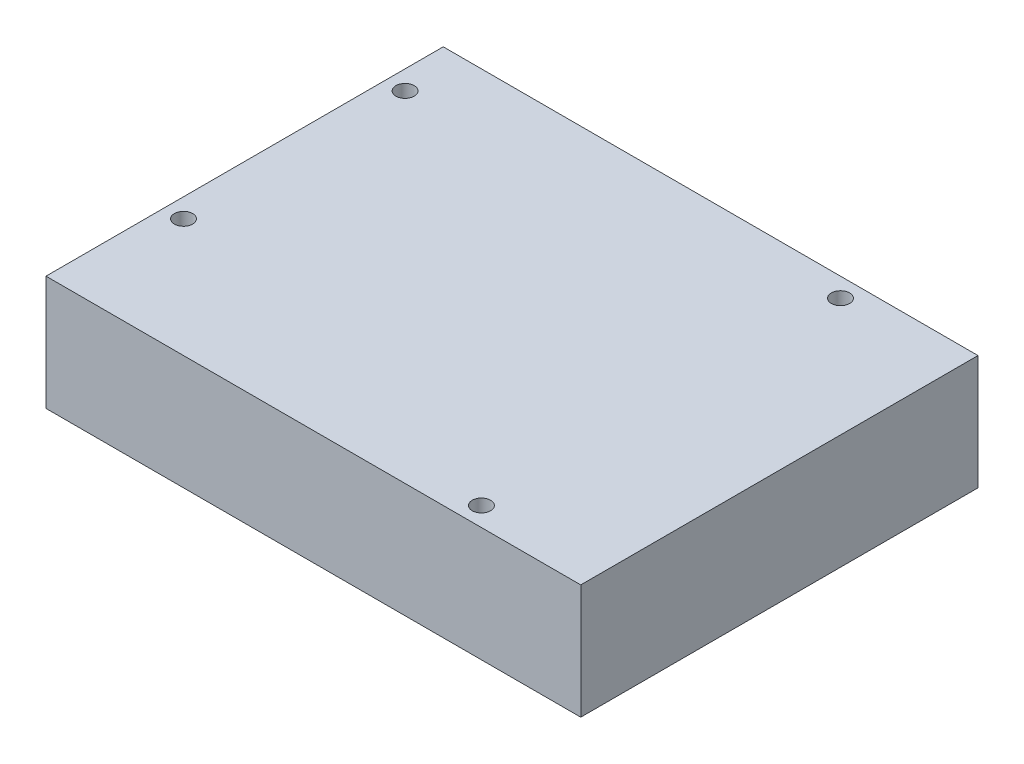
SolidWorks part; units mm, degrees
ref_plane "Piano frontale" through (0, 0, 0) normal (0, 0, 1) x (1, 0, 0)
ref_plane "Piano superiore" through (0, 0, 0) normal (0, 1, 0) x (1, 0, 0)
ref_plane "Piano destro" through (0, 0, 0) normal (1, 0, 0) x (0, 0, -1)
sketch "Schizzo2" plane through (0, 0, 0) normal (0, 1, 0) x (1, 0, 0)
  line L1 (-35, 26) -> (35, 26)
  line L2 (-35, 26) -> (-35, -26)
  line L3 (-35, -26) -> (35, -26)
  line L4 (35, 26) -> (35, -26)
  line L5 (-35, 26) -> (35, -26) construction
  line L6 (-35, -26) -> (35, 26) construction
  point P0 (0, 0)
  dimension "D1" = 70
  dimension "D2" = 52
extrude "Estrusione-Estrusione1" add sketch "Schizzo2" along normal blind 15
hole_wizard "Foro per Vite M2-1" positions "Schizzo3" profile "Schizzo4" hole size "M2" standard "ISO" end condition through all
sketch "Schizzo3" plane through (0, 15, 0) normal (0, 1, 0) x (1, 0, 0)
  line L0 (35, 26) -> (-35, 26) construction
  line L1 (-35, -26) -> (35, -26) construction
  line L2 (-35, 26) -> (-35, -26) construction
  line L3 (35, -26) -> (35, 26) construction
  point P0 (19.5, -23.5)
  point P2 (19.5, 23.5)
  point P4 (-32.5, 18.5)
  point P6 (-32.5, -10.5)
  dimension "D1" = 2.5
  dimension "D2" = 2.5
  dimension "D3" = 15.5
  dimension "D4" = 7.5
  dimension "D5" = 2.5
  dimension "D6" = 2.5
  dimension "D7" = 15.5
  dimension "D8" = 15.5
sketch "Schizzo4" plane through (19.5, 15, 23.5) normal (1, 0, 0) x (0, 0, 1)
  line L0 (0, 0) -> (0, 15)
  line L1 (0, 15) -> (1.2, 15)
  line L2 (1.2, 15) -> (1.2, 0)
  line L5 (1.2, 0) -> (0, 0)
  line L11 (0, -6.35) -> (0, 107.95) construction
  dimension "Thru Hole Dia." = 2.4
  dimension "Thru Hole Depth" = 15
